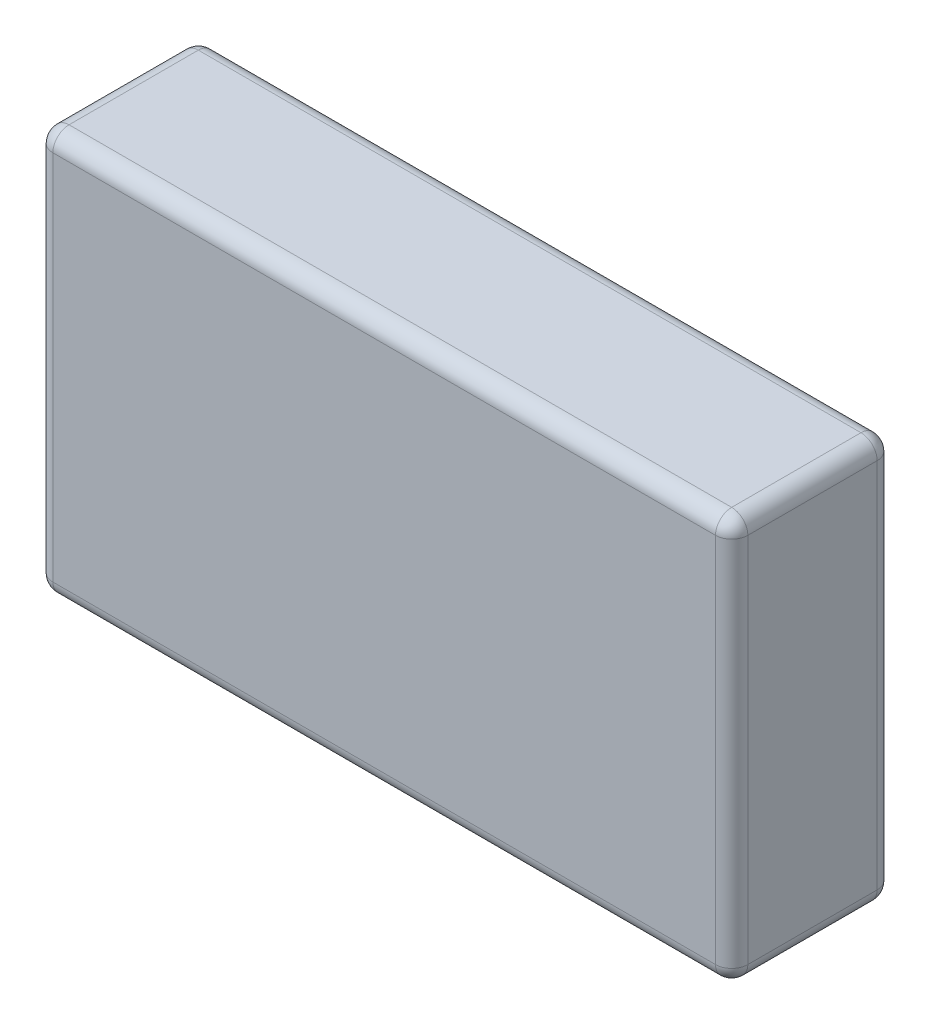
SolidWorks part; units mm, degrees
ref_plane "正面" through (0, 0, 0) normal (0, 0, 1) x (1, 0, 0)
ref_plane "平面" through (0, 0, 0) normal (0, 1, 0) x (1, 0, 0)
ref_plane "右側面" through (0, 0, 0) normal (1, 0, 0) x (0, 0, -1)
sketch "ｽｹｯﾁ1" plane through (0, 0, 0) normal (0, 0, 1) x (1, 0, 0)
  line L1 (-21.5, -12.5) -> (21.5, -12.5)
  line L2 (-21.5, -12.5) -> (-21.5, 12.5)
  line L3 (-21.5, 12.5) -> (21.5, 12.5)
  line L4 (21.5, -12.5) -> (21.5, 12.5)
  line L5 (-21.5, -12.5) -> (21.5, 12.5) construction
  line L6 (-21.5, 12.5) -> (21.5, -12.5) construction
  point P0 (0, 0)
  dimension "D1" = 25
  dimension "D2" = 43
extrude "ﾎﾞｽ - 押し出し1" add sketch "ｽｹｯﾁ1" along normal blind 10
fillet "ﾌｨﾚｯﾄ1" radius 1 12 edges at (-21.5, 12.5, 5) (21.5, 12.5, 5) (0, 12.5, 0) (-21.5, 0, 0) (21.5, 0, 0) (-21.5, -12.5, 5) (21.5, -12.5, 5) (0, -12.5, 0) (0, -12.5, 10) (-21.5, 0, 10) (0, 12.5, 10) (21.5, 0, 10)
